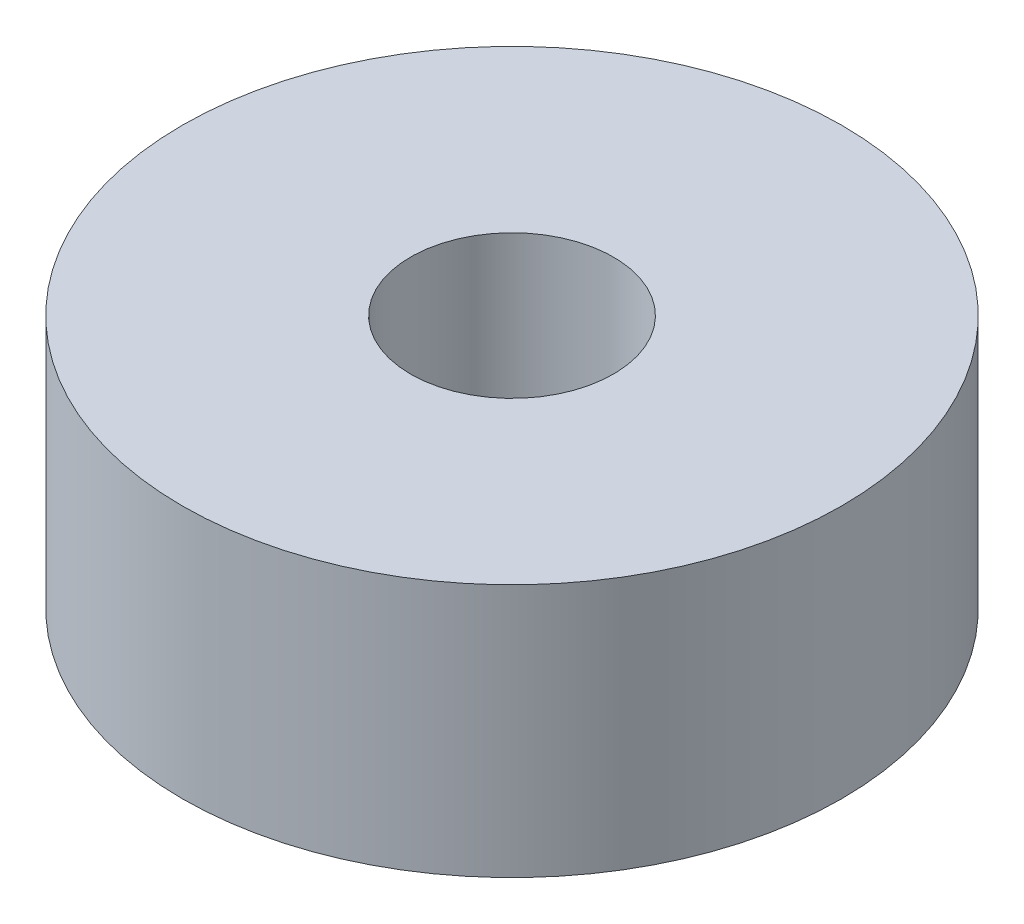
SolidWorks part; units mm, degrees
ref_plane "Front Plane" through (0, 0, 0) normal (0, 0, 1) x (1, 0, 0)
ref_plane "Top Plane" through (0, 0, 0) normal (0, 1, 0) x (1, 0, 0)
ref_plane "Right Plane" through (0, 0, 0) normal (1, 0, 0) x (0, 0, -1)
sketch "Sketch1" plane through (0, 0, 0) normal (0, 1, 0) x (1, 0, 0)
  circle A0 centre (0, 0) radius 2
  circle A1 centre (0, 0) radius 6.5
extrude "Boss-Extrude1" add sketch "Sketch1" along normal blind 5
